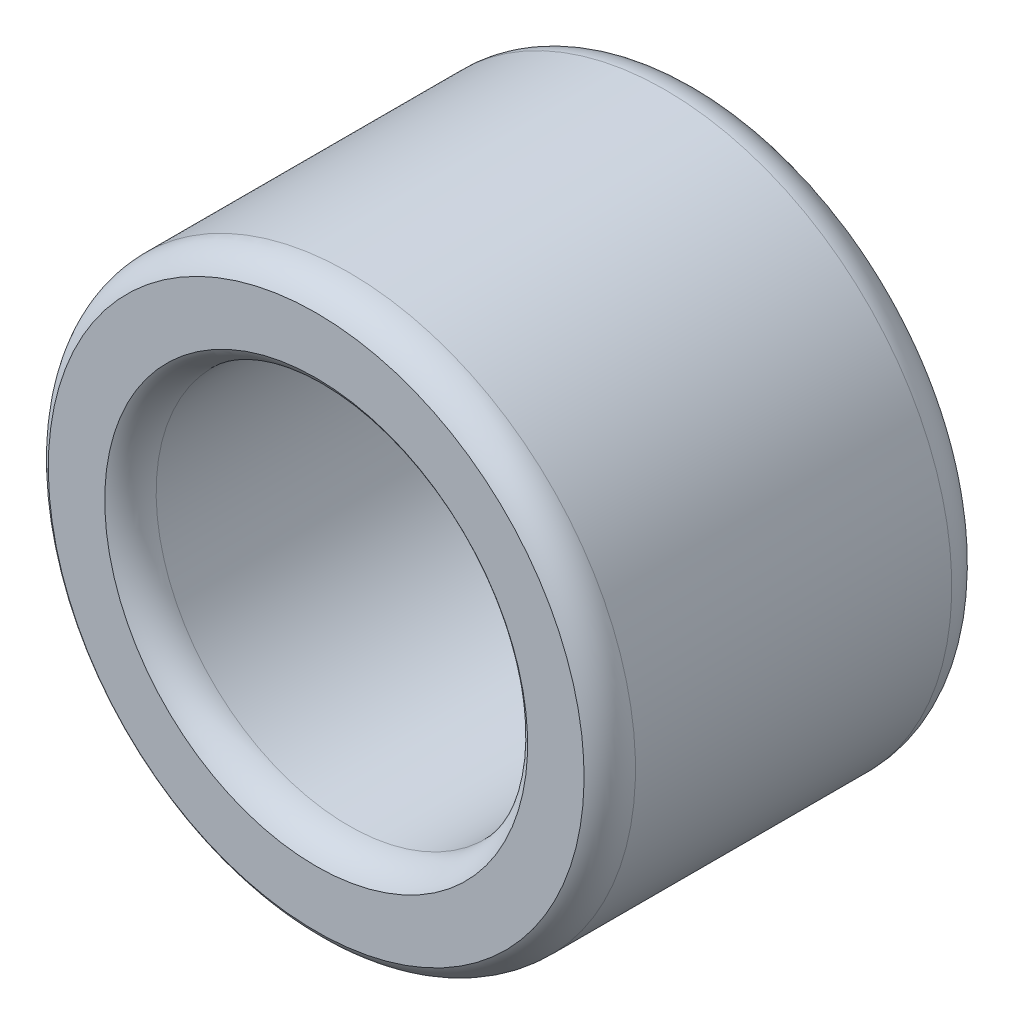
SolidWorks part; units mm, degrees
ref_plane "Front Plane" through (0, 0, 0) normal (0, 0, 1) x (1, 0, 0)
ref_plane "Top Plane" through (0, 0, 0) normal (0, 1, 0) x (1, 0, 0)
ref_plane "Right Plane" through (0, 0, 0) normal (1, 0, 0) x (0, 0, -1)
sketch "Sketch1" plane through (0, 0, 0) normal (0, 0, 1) x (1, 0, 0)
  line L0 (-3.2067, 0) -> (3.2067, 0) construction
  line L1 (-4.7727, 0) -> (4.7727, 0) construction
  point P4 (0, 0)
  point P8 (0, 0)
  point P9 (-3.2067, 0)
  point P10 (3.2067, 0)
  point P11 (4.7727, 0)
  point P12 (-4.7727, 0)
  dimension "ID" = 6.4135
  dimension "OD" = 9.5453
sketch "Sketch2" plane through (0, 0, 0) normal (1, 0, 0) x (0, 0, -1)
  line L0 (0, 4.7727) -> (0, -4.7727) construction
  line L1 (-3.175, 4.7727) -> (3.175, 4.7727) construction
  point P4 (0, 0)
  point P7 (0, 4.7727)
  point P9 (-3.175, 4.7727)
  point P10 (3.175, 4.7727)
  dimension "D1" = 9.5453
  dimension "Length" = 6.35
sketch "Sketch3" plane through (0, 0, 0) normal (0, 0, 1) x (1, 0, 0)
  circle A0 centre (0, 0) radius 3.2068
  circle A1 centre (0, 0) radius 4.7727
extrude "Boss-Extrude1" add sketch "Sketch3" along normal mid plane 6.35
sketch "Sketch4" plane through (0, 0, 0) normal (1, 0, 0) x (0, 0, -1)
  line L0 (3.175, 0) -> (-3.175, 0) construction
  line L1 (-3.175, 3.2067) -> (-3.175, -3.2068) construction
  line L2 (0, 4.7727) -> (0, -4.7727) construction
  line L3 (-3.175, -4.7727) -> (3.175, -4.7727) construction
  line L4 (-3.175, 3.2067) -> (3.175, 3.2067) construction
  line L5 (-3.175, 4.7727) -> (3.175, 4.7727) construction
  line L6 (-3.175, 4.7727) -> (-3.175, -4.7727) construction
  line L7 (-3.175, 4.7727) -> (3.175, 4.7727) construction
  line L8 (-2.6326, 4.7727) -> (-2.6326, 3.2067) construction
  line L9 (-2.6326, 4.7727) -> (-3.175, 4.7727)
  line L10 (-3.175, 4.7727) -> (-3.175, 4.4595)
  line L11 (-2.6326, 3.2067) -> (-3.175, 3.2067)
  line L12 (-3.175, 3.2067) -> (-3.175, 3.5199)
  line L13 (-3.175, 4.4595) -> (-3.8983, 3.2067) construction
  line L14 (3.175, 3.2067) -> (3.175, 3.5199)
  line L15 (2.6326, 3.2067) -> (3.175, 3.2067)
  line L16 (3.175, 4.7727) -> (3.175, 4.4595)
  line L17 (2.6326, 4.7727) -> (3.175, 4.7727)
  arc A0 (-2.6326, 4.7727) -> (-3.175, 4.4595) centre (-2.6326, 4.1463) ccw
  arc A1 (-2.6326, 3.2067) -> (-3.175, 3.5199) centre (-2.6326, 3.8331) cw
  arc A2 (2.6326, 3.2067) -> (3.175, 3.5199) centre (2.6326, 3.8331) ccw
  arc A3 (2.6326, 4.7727) -> (3.175, 4.4595) centre (2.6326, 4.1463) cw
  point P4 (0, 0)
  point P7 (-3.175, 0)
  dimension "D1" = 6.4135
  dimension "D2" = 6.35
  dimension "D3" = 0.3132
  dimension "D4" = 30
revolve "Cut-Revolve1" cut sketch "Sketch4" angle 360 about L0
equation "\"D1@Sketch2\"=\"OD@sketch1\""
equation "\"D1@Boss-Extrude1\"=\"Length@sketch2\""
equation "\"D1@Sketch4\"=\"ID@sketch1\""
equation "\"D2@Sketch4\"=\"Length@sketch2\""
equation "\"D3@Sketch4\"=((\"OD@sketch1\"-\"ID@sketch1\")/2)*.2"
